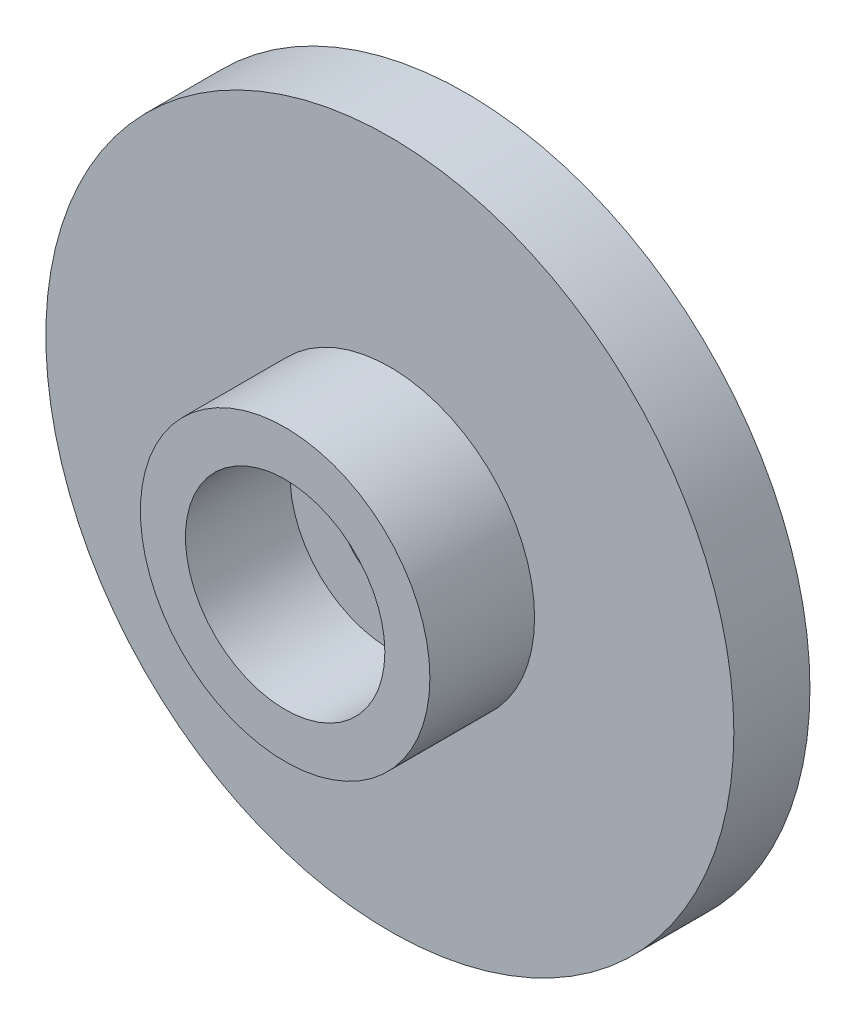
SolidWorks part; units mm, degrees
ref_plane "Ön Düzlem" through (0, 0, 0) normal (0, 0, 1) x (1, 0, 0)
ref_plane "Üst Düzlem" through (0, 0, 0) normal (0, 1, 0) x (1, 0, 0)
ref_plane "Sağ Düzlem" through (0, 0, 0) normal (1, 0, 0) x (0, 0, -1)
sketch "Sketch1" plane through (0, 0, 0) normal (0, 0, 1) x (1, 0, 0)
  circle A0 centre (0, 0) radius 10.35
  dimension "D1" = 20.7
extrude "Boss-Extrude1" add sketch "Sketch1" along normal blind 2.29
sketch "Sketch2" plane through (0, 0, 2.29) normal (0, 0, 1) x (1, 0, 0)
  circle A0 centre (0, 0) radius 4.355
  dimension "D1" = 8.71
extrude "Boss-Extrude2" add sketch "Sketch2" along normal blind 3.15
sketch "Sketch3" plane through (0, 0, 5.44) normal (0, 0, 1) x (1, 0, 0)
  circle A0 centre (0, 0) radius 3
  dimension "D1" = 6
extrude "Cut-Extrude1" cut sketch "Sketch3" against normal up to surface (3.15 mm away) up to face at (10.35, 0, 2.29)
sketch "Sketch4" plane through (0, 0, 2.29) normal (0, 0, 1) x (1, 0, 0)
  circle A0 centre (0, 0) radius 1.5
  dimension "D1" = 3
extrude "Cut-Extrude2" cut sketch "Sketch4" against normal up to surface (2.29 mm away) up to face at (10.35, 0, 0)
